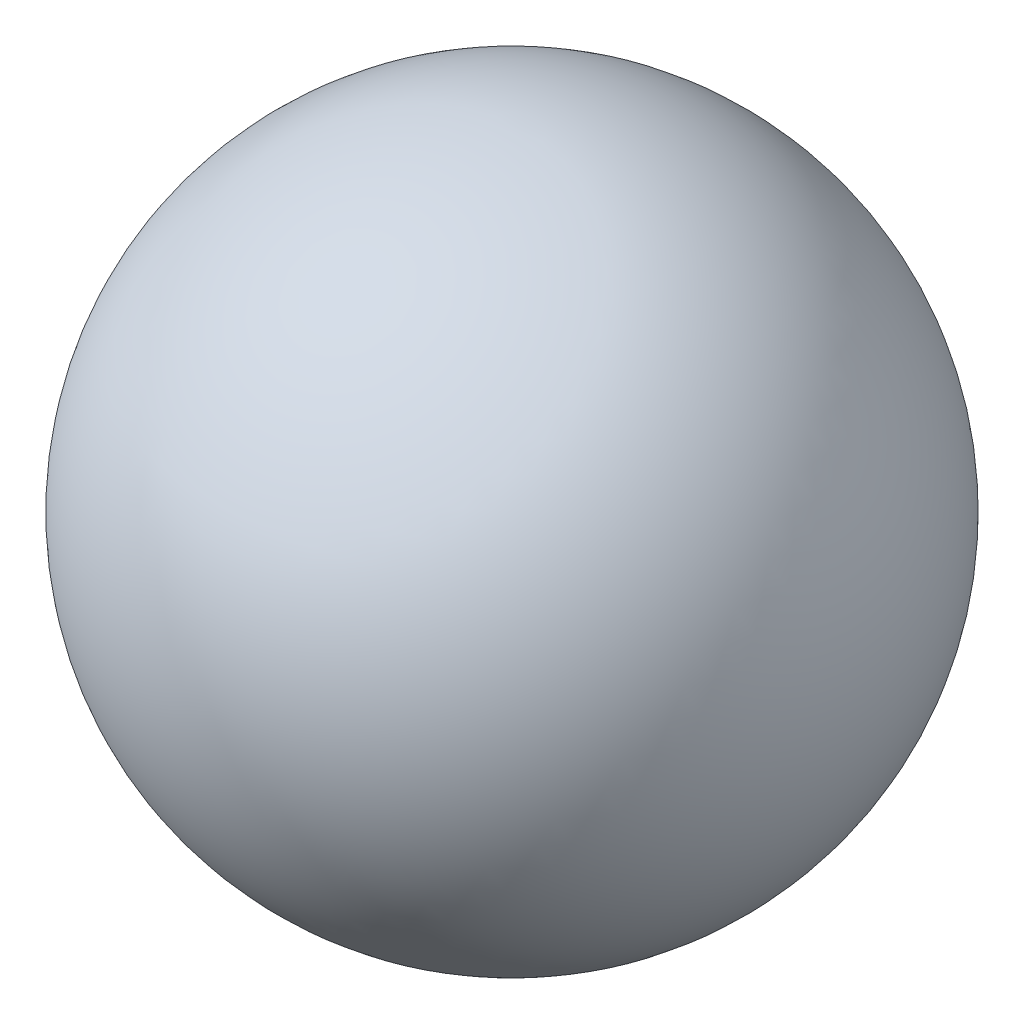
SolidWorks part; units mm, degrees
ref_plane "Přední rovina" through (0, 0, 0) normal (0, 0, 1) x (1, 0, 0)
ref_plane "Horní rovina" through (0, 0, 0) normal (0, 1, 0) x (1, 0, 0)
ref_plane "Pravá rovina" through (0, 0, 0) normal (1, 0, 0) x (0, 0, -1)
sketch "Skica1" plane through (0, 0, 0) normal (0, 0, 1) x (1, 0, 0)
  line L0 (0, -7.7164) -> (0, 8.5546) construction
  line L1 (0, 6.325) -> (0, -6.325)
  arc A0 (0, 6.325) -> (0, -6.325) centre (0, 0) ccw
  dimension "D1" = 12.65
revolve "Rotovat1" add sketch "Skica1" angle 360 about L0
